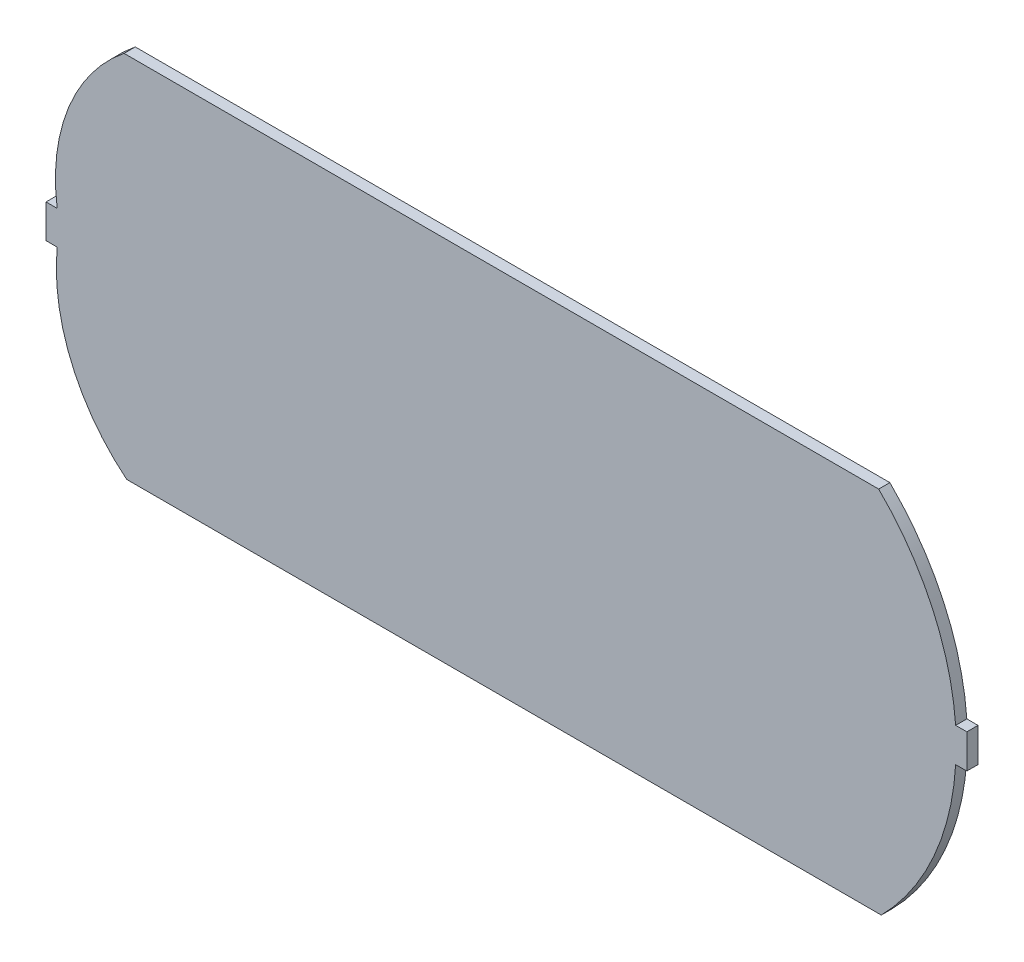
SolidWorks part; units mm, degrees
ref_plane "Front Plane" through (0, 0, 0) normal (0, 0, 1) x (1, 0, 0)
ref_plane "Top Plane" through (0, 0, 0) normal (0, 1, 0) x (1, 0, 0)
ref_plane "Right Plane" through (0, 0, 0) normal (1, 0, 0) x (0, 0, -1)
sketch "cover" plane through (0, 0, 0) normal (0, 0, 1) x (1, 0, 0)
  line L2 (20.4446, -0.8509) -> (87.9446, -0.8509)
  line L7 (87.9446, -0.8509) -> (20.4446, -0.8509)
  line L8 (20.676, -33.7387) -> (88.176, -33.7387)
  line L9 (95.8284, -18.7564) -> (94.8284, -18.7564)
  line L10 (14.4607, -18.8501) -> (13.4607, -18.8501)
  line L12 (14.4607, -15.8501) -> (13.4607, -15.8501)
  line L13 (13.4607, -18.8501) -> (13.4607, -15.8501)
  line L14 (95.8284, -18.7564) -> (95.8284, -15.7151)
  line L15 (95.8284, -15.7151) -> (94.8284, -15.7151)
  line L17 (94.8284, -15.7151) -> (95.8284, -15.7151)
  line L18 (95.8284, -18.7564) -> (94.8284, -18.7564)
  line L19 (14.4607, -15.8501) -> (13.4607, -15.8501)
  line L20 (13.4607, -18.8501) -> (14.4607, -18.8501)
  arc A3 (20.4446, -0.8509) -> (14.4607, -15.8501) centre (30.6292, -13.6073) ccw
  arc A4 (87.9446, -0.8509) -> (94.8284, -15.7151) centre (71.6396, -17.4281) cw
  arc A5 (94.8284, -18.7564) -> (88.176, -33.7387) centre (71.6396, -17.4281) cw
  arc A6 (14.4607, -18.8501) -> (20.676, -33.7387) centre (31.475, -20.489) ccw
  point P6 (30.7054, -36.1984)
  point P10 (94.8284, -18.7564)
  point P11 (95.8284, -18.7564)
  point P12 (94.8284, -15.7151)
  point P13 (95.8284, -15.7151)
  point P14 (13.4607, -15.8501)
  point P16 (13.4607, -18.8501)
  point P23 (14.4607, -18.8501)
  point P24 (14.4607, -15.8501)
  point P25 (15.2054, -18.4502)
  dimension "D3" = 3
  dimension "D2" = 1
  dimension "D6" = 67.5
  dimension "D7" = 1
  dimension "D8" = 1
  dimension "D9" = 1
  dimension "D10" = 3.0413
  dimension "D15" = 67.5
extrude "Boss-Extrude1" add sketch "cover" along normal blind 1
